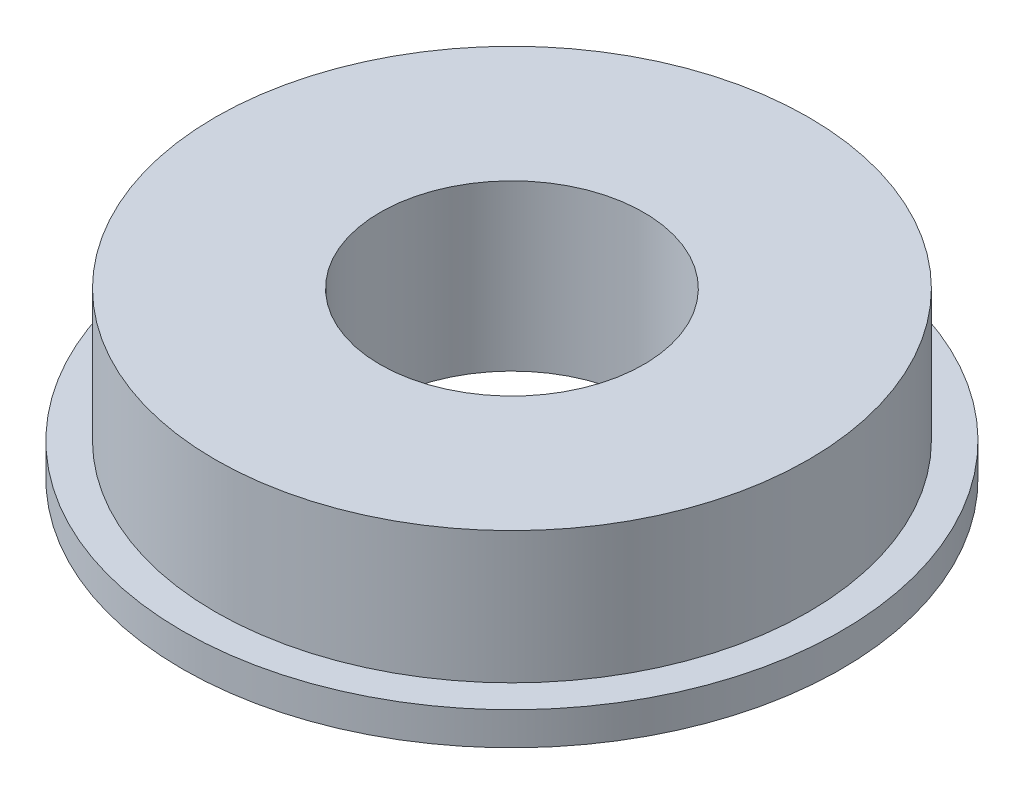
SolidWorks part; units mm, degrees
ref_plane "Front Plane" through (0, 0, 0) normal (0, 0, 1) x (1, 0, 0)
ref_plane "Top Plane" through (0, 0, 0) normal (0, 1, 0) x (1, 0, 0)
ref_plane "Right Plane" through (0, 0, 0) normal (1, 0, 0) x (0, 0, -1)
sketch "Sketch1" plane through (0, 0, 0) normal (0, 1, 0) x (1, 0, 0)
  circle A0 centre (0, 0) radius 15.875
  dimension "D1" = 31.75
extrude "Boss-Extrude1" add sketch "Sketch1" along normal blind 1.5875
sketch "Sketch2" plane through (0, 1.5875, 0) normal (0, 1, 0) x (1, 0, 0)
  circle A0 centre (0, 0) radius 14.2875
  dimension "D1" = 28.575
extrude "Boss-Extrude2" add sketch "Sketch2" along normal blind 6.35
sketch "Sketch4" plane through (0, 7.9375, 0) normal (0, 1, 0) x (1, 0, 0)
  circle A0 centre (0, 0) radius 6.35
extrude "Cut-Extrude1" cut sketch "Sketch4" against normal through all
